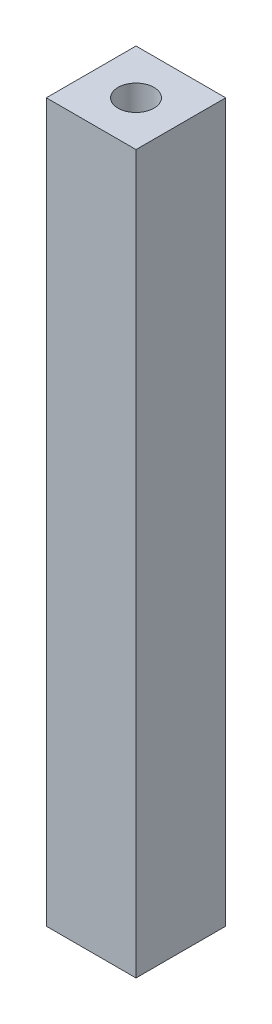
SolidWorks part; units mm, degrees
ref_plane "Front Plane" through (0, 0, 0) normal (0, 0, 1) x (1, 0, 0)
ref_plane "Top Plane" through (0, 0, 0) normal (0, 1, 0) x (1, 0, 0)
ref_plane "Right Plane" through (0, 0, 0) normal (1, 0, 0) x (0, 0, -1)
sketch "Sketch1" plane through (0, 0, 0) normal (0, 1, 0) x (1, 0, 0)
  line L1 (0, 0) -> (12.7, 0)
  line L2 (0, 0) -> (0, -12.7)
  line L3 (0, -12.7) -> (12.7, -12.7)
  line L4 (12.7, 0) -> (12.7, -12.7)
  dimension "D1" = 12.7
  dimension "D2" = 12.7
extrude "Boss-Extrude1" add sketch "Sketch1" along normal blind 101.6
sketch "Sketch4" plane through (0, 101.6, 0) normal (0, 1, 0) x (1, 0, 0)
  line L0 (12.7, 0) -> (0, 0) construction
  line L1 (0, 0) -> (0, -12.7) construction
  point P0 (6.35, -6.35)
  point P5 (6.35, -6.35)
  dimension "D1" = 6.35
  dimension "D2" = 6.35
sketch "Sketch5" plane through (0, 0, 0) normal (0, -1, 0) x (1, 0, 0)
  line L0 (12.7, 12.7) -> (12.7, 0) construction
  line L1 (0, 12.7) -> (12.7, 12.7) construction
  point P0 (6.35, 6.35)
  dimension "D1" = 6.35
  dimension "D2" = 6.35
hole_wizard "1/4-20 Tapped Hole1" positions "3DSketch1" profile "Sketch7" tap size "1/4-20" standard "ANSI Inch"
sketch3d "3DSketch1"
  point P0 (6.35, 0, 6.35)
  point P3 (6.35, 101.6, 6.35)
sketch "Sketch7" plane through (6.35, 0, 6.35) normal (1, 0, 0) x (0, 0, -1)
  line L0 (0, 0) -> (0, 18.0438)
  line L1 (0, 18.0438) -> (2.5527, 16.51)
  line L2 (2.5527, 16.51) -> (2.5527, 0)
  line L5 (2.5527, 0) -> (0, 0)
  line L10 (0, 18.0438) -> (-2.5527, 16.51) construction
  line L11 (0, -6.35) -> (0, 107.95) construction
  dimension "Tap Drill Dia." = 5.1054
  dimension "Tap Drill Depth" = 16.51
  dimension "Drill Angle" = 118
cosmetic thread "Hole Thread1" parameters "D1"=12.7, "D2"=6.35
cosmetic thread "Hole Thread2" parameters "D1"=12.7, "D2"=6.35
